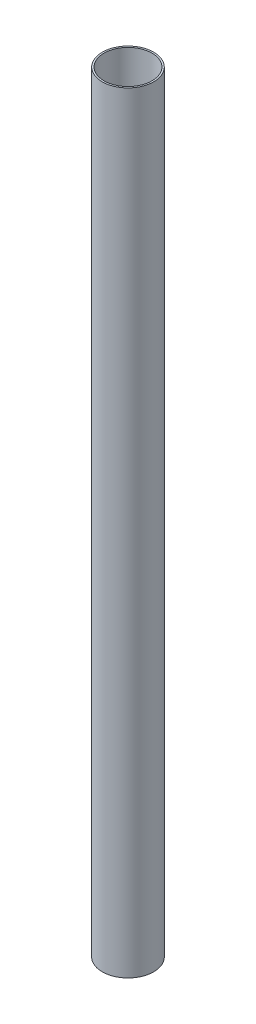
SolidWorks part; units mm, degrees
material "AISI 4130 Steel, annealed at 865C"
ref_plane "X-Y Datum" through (0, 0, 0) normal (0, 0, 1) x (1, 0, 0)
ref_plane "X-Z Datum" through (0, 0, 0) normal (0, 1, 0) x (1, 0, 0)
ref_plane "Y-Z Datum" through (0, 0, 0) normal (1, 0, 0) x (0, 0, -1)
sketch "Sketch1" plane through (0, 0, 0) normal (0, 1, 0) x (1, 0, 0)
  circle A0 centre (0, 0) radius 11.8745
  circle A1 centre (0, 0) radius 12.7
  dimension "D1" = 25.4
  dimension "D2" = 23.749
extrude "Boss-Extrude1" add sketch "Sketch1" along normal blind 381
